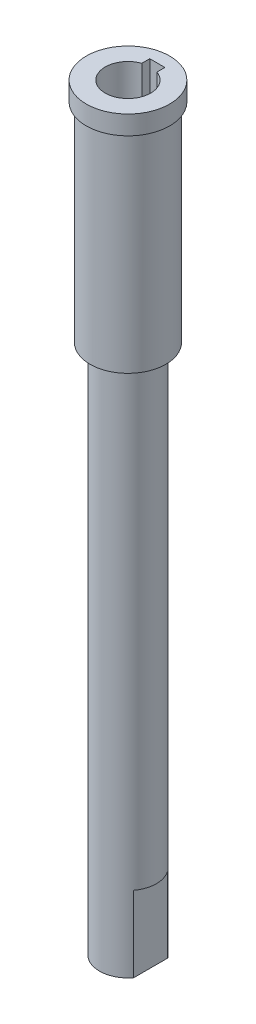
SolidWorks part; units mm, degrees
material "AISI 304"
ref_plane "前视基准面" through (0, 0, 0) normal (0, 0, 1) x (1, 0, 0)
ref_plane "上视基准面" through (0, 0, 0) normal (0, 1, 0) x (1, 0, 0)
ref_plane "右视基准面" through (0, 0, 0) normal (1, 0, 0) x (0, 0, -1)
sketch "Sketch2" plane through (0, 0, 0) normal (0, 1, 0) x (1, 0, 0)
  circle A0 centre (0, 0) radius 10
  dimension "D1" = 20
extrude "Extrude1" add sketch "Sketch2" along normal blind 200
sketch "Sketch3" plane through (0, 200, 0) normal (0, 1, 0) x (1, 0, 0)
  line L2 (2, 5.6569) -> (2, 7.7493)
  line L3 (2, 7.7493) -> (-2, 7.7493)
  line L4 (-2, 5.6569) -> (-2, 7.7493)
  line L5 (2.9935, 3.3817) -> (-2, 7.7493) construction
  line L6 (2, 7.7493) -> (-2.9935, 3.3817) construction
  arc A0 (-2, 5.6569) -> (2, 5.6569) centre (0, 0) ccw
  point P3 (0, 6)
  dimension "D1" = 12
  dimension "D2" = 4
extrude "Extrude2" cut sketch "Sketch3" against normal blind 30
sketch "Sketch5" plane through (0, 0, 0) normal (0, -1, 0) x (1, 0, 0)
  circle A0 centre (0, 0) radius 7.5
  circle A2 centre (0, 0) radius 10 construction
  dimension "D1" = 2.5
extrude "Extrude4" cut sketch "Sketch5" against normal blind 140 flip side to cut
sketch "Sketch6" plane through (0, 200, 0) normal (0, 1, 0) x (1, 0, 0)
  circle A0 centre (0, 0) radius 8.6307
  circle A1 centre (0, 0) radius 11
  circle A2 centre (0, 0) radius 10 construction
  dimension "D1" = 1
extrude "Extrude5" add sketch "Sketch6" against normal blind 5
sketch "Sketch7" plane through (0, 0, 0) normal (0, -1, 0) x (1, 0, 0)
  line L1 (17.8671, 23.4714) -> (6, 23.4714)
  line L2 (17.8671, 23.4714) -> (17.8671, -10.1519)
  line L3 (17.8671, -10.1519) -> (6, -10.1519)
  line L4 (6, 23.4714) -> (6, -10.1519)
  line L5 (17.8671, 23.4714) -> (6, -10.1519) construction
  line L6 (17.8671, -10.1519) -> (6, 23.4714) construction
  point P0 (11.9335, 6.6598)
  dimension "D1" = 6
extrude "Extrude6" cut sketch "Sketch7" against normal blind 20
